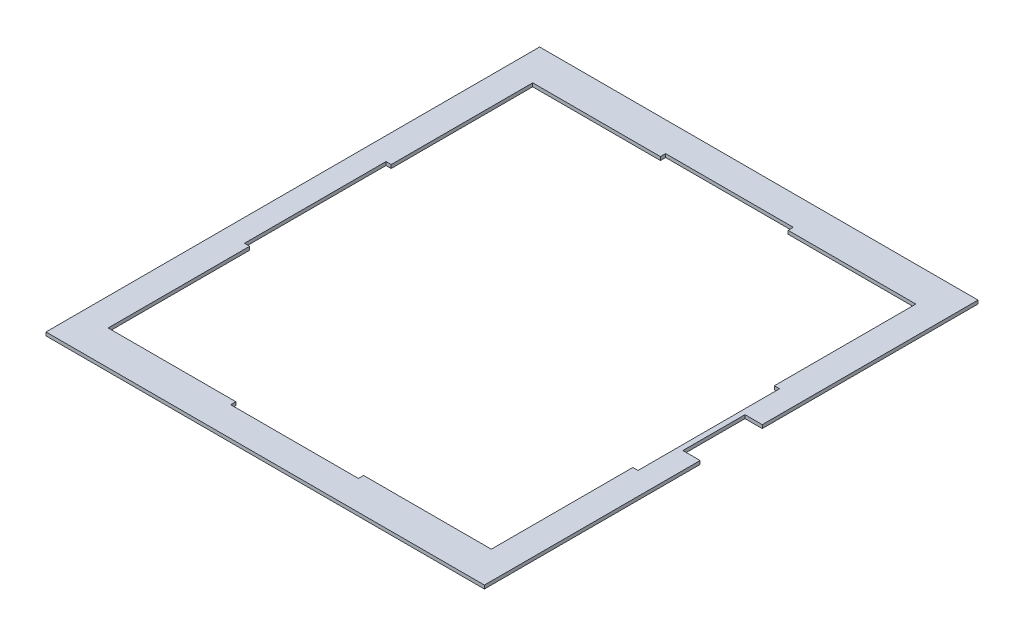
SolidWorks part; units mm, degrees
ref_plane "Front Plane" through (0, 0, 0) normal (0, 0, 1) x (1, 0, 0)
ref_plane "Top Plane" through (0, 0, 0) normal (0, 1, 0) x (1, 0, 0)
ref_plane "Right Plane" through (0, 0, 0) normal (1, 0, 0) x (0, 0, -1)
sketch "Sketch1" plane through (0, 0, 0) normal (0, 1, 0) x (1, 0, 0)
  line L0 (37, 123) -> (111, 123)
  line L1 (-111, -123) -> (-37, -123)
  line L2 (-111, -123) -> (-111, -41)
  line L3 (-111, 123) -> (-37, 123)
  line L4 (111, -123) -> (111, -41)
  line L5 (-111, -123) -> (111, 123) construction
  line L6 (-111, 123) -> (111, -123) construction
  line L7 (-127, -143) -> (127, -143)
  line L8 (-127, -143) -> (-127, 143)
  line L9 (-127, 143) -> (127, 143)
  line L10 (127, -143) -> (127, -18)
  line L11 (-127, -143) -> (127, 143) construction
  line L12 (-127, 143) -> (127, -143) construction
  line L13 (111, 41) -> (111, 123)
  line L14 (37, 123) -> (37, 126)
  line L15 (37, 126) -> (-37, 126)
  line L16 (-37, 123) -> (-37, 126)
  line L17 (-111, 41) -> (-111, 123)
  line L18 (37, -123) -> (37, -126)
  line L19 (37, -126) -> (-37, -126)
  line L20 (-37, -123) -> (-37, -126)
  line L21 (-111, -41) -> (-114, -41)
  line L22 (127, 18) -> (127, 143)
  line L23 (-111, 41) -> (-114, 41)
  line L24 (-114, -41) -> (-114, 41)
  line L25 (111, -41) -> (114, -41)
  line L26 (37, -123) -> (111, -123)
  line L27 (111, 41) -> (114, 41)
  line L28 (114, -41) -> (114, 41)
  line L29 (127, -18) -> (117, -18)
  line L31 (127, 18) -> (117, 18)
  line L32 (117, -18) -> (117, 18)
  point P0 (0, 0)
  point P5 (0, 0)
  dimension "D1" = 222
  dimension "D2" = 246
  dimension "D3" = 20
  dimension "D4" = 16
  dimension "D5" = 3
  dimension "D6" = 10
  dimension "D7" = 36
extrude "Boss-Extrude1" add sketch "Sketch1" along normal blind 2
equation "\"Resolution Projector X\"= 1920"
equation "\"Resolution Projector Y\"= 1080"
equation "\"Resolution Build\"= 0.1"
equation "\"Size Build Volume X\"= \"Resolution Projector X\" * \"Resolution Build\""
equation "\"Size Build Volume Y\"= 2 * \"Resolution Projector Y\" * \"Resolution Build\""
equation "\"Size Build Volume Z\"= \"Size Build Volume Y\""
equation "\"Thick\"= 0.125in"
equation "\"Size Enclosure Internal X\"= 350mm"
equation "\"Size Enclosure Internal Y\"= \"Size Enclosure Internal X\""
equation "\"Size Enclosure Internal Z\"= \"Size Enclosure Internal X\""
equation "\"Size Enclosure External Z\"= 1000mm"
equation "\"Diameter Screw\"= 3mm"
equation "\"Diameter Nut\"= 5.5mm"
equation "\"Thick Nut\"= 2.5mm"
equation "\"Length Screw\"= 12mm"
equation "\"D1@Sketch1\"=\"Size Build Volume X\"+30"
equation "\"D2@Sketch1\"=\"Size Build Volume Y\"+30"
equation "\"D4@Sketch1\"=16"
